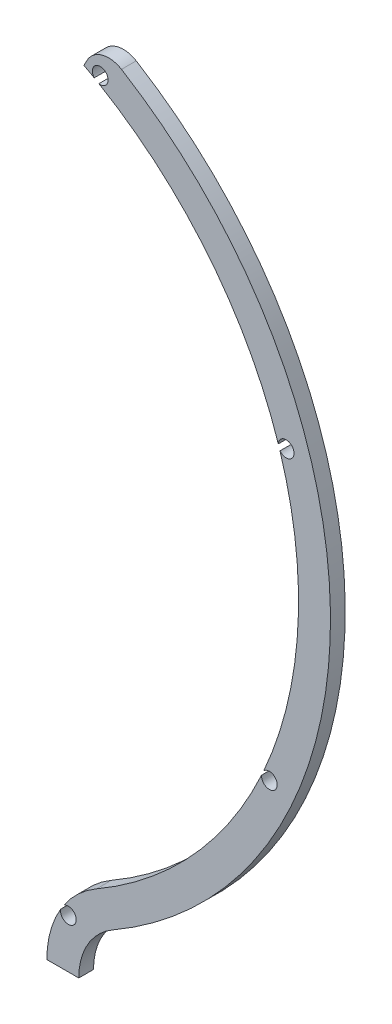
SolidWorks part; units mm, degrees
material "6061 Alloy"
ref_plane "Front Plane" through (0, 0, 0) normal (0, 0, 1) x (1, 0, 0)
ref_plane "Top Plane" through (0, 0, 0) normal (0, 1, 0) x (1, 0, 0)
ref_plane "Right Plane" through (0, 0, 0) normal (1, 0, 0) x (0, 0, -1)
sketch "Sketch1" plane through (0, 0, 0) normal (0, 0, 1) x (1, 0, 0)
  line L0 (23.5, 0) -> (35.5, 0) construction
  line L1 (31, 0) -> (37.5, 0)
  line L3 (39.1768, 162.602) -> (38.5438, 161.4089)
  circle A0 centre (41.8718, 161.2805) radius 1.6
  circle A1 centre (79.7216, 114.3972) radius 1.6
  circle A2 centre (76.2992, 54.2395) radius 1.6
  circle A3 centre (35.3905, 10) radius 1.6
  arc A4 (38.5438, 161.4089) -> (41.1218, 17.5314) centre (0, 88.7564) cw
  arc A5 (41.1218, 17.5314) -> (31, 0) centre (51.2436, 0) ccw
  arc A6 (43.3718, 13.6343) -> (35.5, 0) centre (51.2436, 0) ccw construction
  arc A7 (43.3718, 13.6343) -> (15.0629, 174.1822) centre (0, 88.7564) ccw construction
  arc A8 (46.1965, 164.5278) -> (44.3718, 11.9023) centre (0, 88.7564) cw
  arc A9 (44.3718, 11.9023) -> (37.5, 0) centre (51.2436, 0) ccw
  arc A10 (46.1965, 164.5278) -> (39.1768, 162.602) centre (43.5937, 160.2587) ccw
  point P31 (0, 88.7564)
  dimension "D1" = 3.2
  dimension "D2" = 4.5
  dimension "D3" = 2
  dimension "D5" = 5
  dimension "D4" = 3
extrude "Boss-Extrude1" add sketch "Sketch1" along normal blind 3 contours A8 A10 L3 A4 A0 A1 A2 A5 A3 L1 A9
